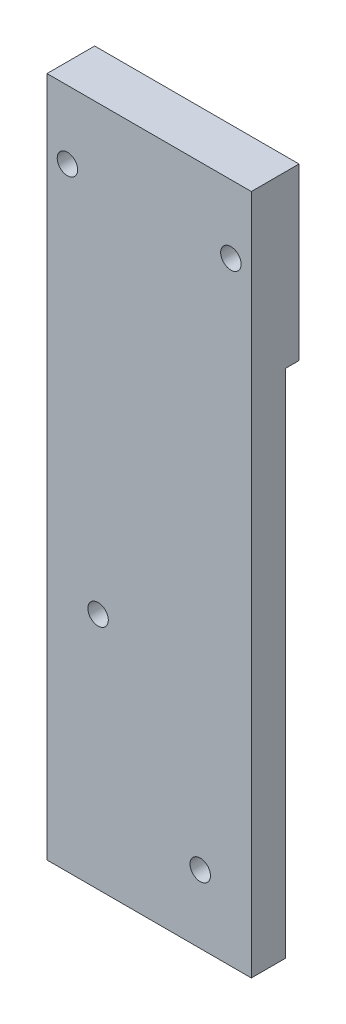
SolidWorks part; units mm, degrees
ref_plane "Alzado" through (0, 0, 0) normal (0, 0, 1) x (1, 0, 0)
ref_plane "Planta" through (0, 0, 0) normal (0, 1, 0) x (1, 0, 0)
ref_plane "Vista lateral" through (0, 0, 0) normal (1, 0, 0) x (0, 0, -1)
sketch "Croquis1" plane through (0, 0, 0) normal (0, 0, 1) x (1, 0, 0)
  line L0 (65.454, -1015) -> (65.454, -1005)
  line L1 (65.454, -1005) -> (95.454, -1015) construction
  line L2 (65.454, -1005) -> (95.454, -1005)
  line L3 (95.454, -1005) -> (95.454, -1015)
  line L4 (95.454, -1015) -> (95.454, -1105)
  line L5 (95.454, -1105) -> (65.454, -1105)
  line L6 (65.454, -1105) -> (65.454, -1015)
extrude "Saliente-Extruir1" add sketch "Croquis1" along normal blind 5 from offset 2
sketch "Croquis2" plane through (0, 0, 2) normal (0, 0, -1) x (-1, 0, 0)
  line L0 (-95.454, -1005) -> (-65.454, -1005)
  line L1 (-95.454, -1005) -> (-65.454, -1005) construction
  line L2 (-95.454, -1105) -> (-95.454, -1005) construction
  line L3 (-65.454, -1005) -> (-65.454, -1105) construction
  line L4 (-95.454, -1005) -> (-95.454, -1030)
  line L5 (-95.454, -1030) -> (-65.454, -1030)
  line L6 (-65.454, -1030) -> (-65.454, -1005)
extrude "Saliente-Extruir2" add sketch "Croquis2" along normal blind 2
sketch "Croquis3" plane through (0, 0, 2) normal (0, 0, -1) x (-1, 0, 0)
  circle A0 centre (-72.954, -1070) radius 1.5
  circle A1 centre (-87.954, -1095) radius 1.5
extrude "Cortar-Extruir1" cut sketch "Croquis3" against normal blind 10
sketch "Croquis4" plane through (0, 0, 0) normal (0, 0, -1) x (-1, 0, 0)
  circle A0 centre (-92.454, -1015) radius 1.5
  circle A1 centre (-68.454, -1015) radius 1.5
extrude "Cortar-Extruir2" cut sketch "Croquis4" against normal blind 10
sketch "Croquis5" plane through (65.454, 0, 0) normal (-1, 0, 0) x (0, 0, 1)
  line L0 (7, -1005) -> (7, -1105) construction
  line L1 (7, -1005) -> (0, -1005)
  line L2 (7, -1005) -> (7, -1030)
  line L3 (7, -1030) -> (0, -1030)
  line L4 (0, -1005) -> (0, -1030)
  line L5 (0, -1030) -> (0, -1005) construction
